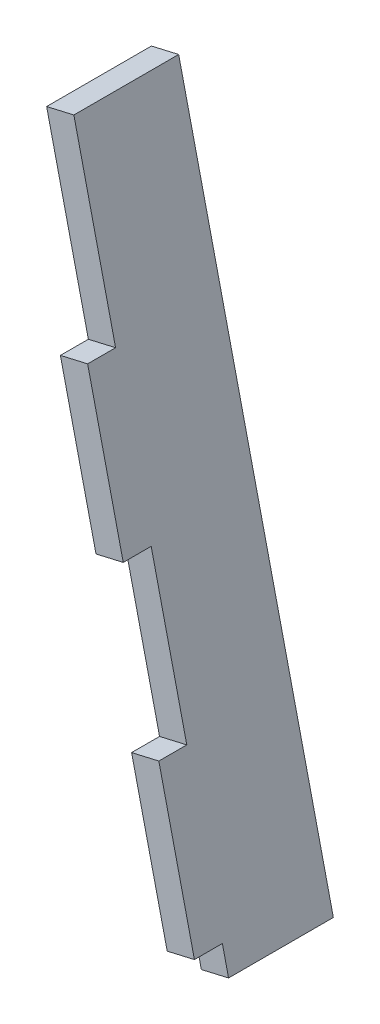
SolidWorks part; units mm, degrees
ref_plane "Front Plane" through (0, 0, 0) normal (0, 0, 1) x (1, 0, 0)
ref_plane "Top Plane" through (0, 0, 0) normal (0, 1, 0) x (1, 0, 0)
ref_plane "Right Plane" through (0, 0, 0) normal (1, 0, 0) x (0, 0, -1)
sketch "Sketch1" plane through (0, 0, 0) normal (0, 0, 1) x (1, 0, 0)
  line L0 (-117.4836, 1583.6084) -> (-107.584, 1585.8939) construction
  line L1 (-81.7027, 1473.7898) -> (-94.6434, 1529.8418) construction
  line L2 (-91.6023, 1471.5043) -> (-81.7027, 1473.7898) construction
  line L3 (-91.6023, 1471.5043) -> (-104.543, 1527.5563) construction
  line L4 (-104.543, 1527.5563) -> (-94.6434, 1529.8418) construction
  line L5 (-120.5247, 1641.946) -> (-107.584, 1585.8939) construction
  line L6 (-130.4243, 1639.6605) -> (-117.4836, 1583.6084) construction
  line L7 (-130.4243, 1639.6605) -> (-120.5247, 1641.946) construction
  line L8 (-120.5247, 1641.946) -> (-107.584, 1585.8939)
  line L9 (-130.4243, 1639.6605) -> (-120.5247, 1641.946)
  line L10 (-130.4243, 1639.6605) -> (-117.4836, 1583.6084)
  line L11 (-117.4836, 1583.6084) -> (-107.584, 1585.8939)
  line L12 (-104.543, 1527.5563) -> (-94.6434, 1529.8418)
  line L13 (-91.6023, 1471.5043) -> (-81.7027, 1473.7898)
  line L14 (-91.6023, 1471.5043) -> (-104.543, 1527.5563)
  line L15 (-81.7027, 1473.7898) -> (-94.6434, 1529.8418)
extrude "Boss-Extrude1" add sketch "Sketch1" against normal blind 10.16
sketch "Sketch2" plane through (0, 0, -10.16) normal (0, 0, -1) x (-1, 0, 0)
  line L0 (145.5906, 1705.3531) -> (89.3528, 1461.7606)
  line L1 (130.4243, 1639.6605) -> (117.4836, 1583.6084) construction
  line L2 (135.691, 1707.6386) -> (79.4532, 1464.0461)
  line L3 (79.4532, 1464.0461) -> (89.3528, 1461.7606)
  line L4 (135.691, 1707.6386) -> (145.5906, 1705.3531)
  line L5 (91.6023, 1471.5043) -> (81.7027, 1473.7898) construction
  dimension "D1" = 10.16
  dimension "D2" = 250
  dimension "D3" = 10
extrude "Boss-Extrude2" add sketch "Sketch2" along normal blind 38.1
